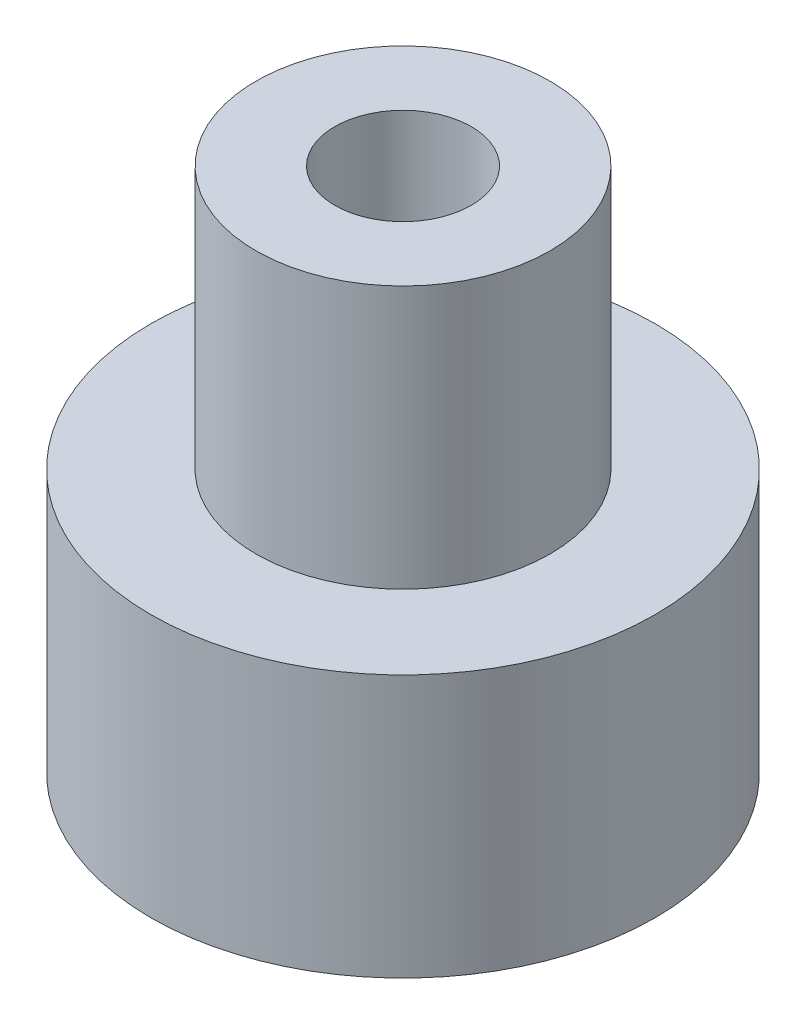
SolidWorks part; units mm, degrees
material "6061 Alloy"
ref_plane "Front Plane" through (0, 0, 0) normal (0, 0, 1) x (1, 0, 0)
ref_plane "Top Plane" through (0, 0, 0) normal (0, 1, 0) x (1, 0, 0)
ref_plane "Right Plane" through (0, 0, 0) normal (1, 0, 0) x (0, 0, -1)
sketch "Sketch1" plane through (0, 0, 0) normal (0, 0, 1) x (1, 0, 0)
  line L0 (-1.3, 5) -> (-2.8, 5)
  line L1 (-2.8, 5) -> (-2.8, 0)
  line L2 (-2.8, 0) -> (-4.8, 0)
  line L3 (-4.8, 0) -> (-4.8, -5)
  line L4 (-4.8, -5) -> (-1.3, -5)
  line L5 (-1.3, 5) -> (-1.3, -5)
  line L6 (0, -1000) -> (0, 49000) construction
  dimension "D1" = 2
  dimension "D2" = 5
  dimension "D3" = 10
  dimension "D4" = 1.3
  dimension "D5" = 1.5
revolve "Revolve1" add sketch "Sketch1" angle 360 about L6
